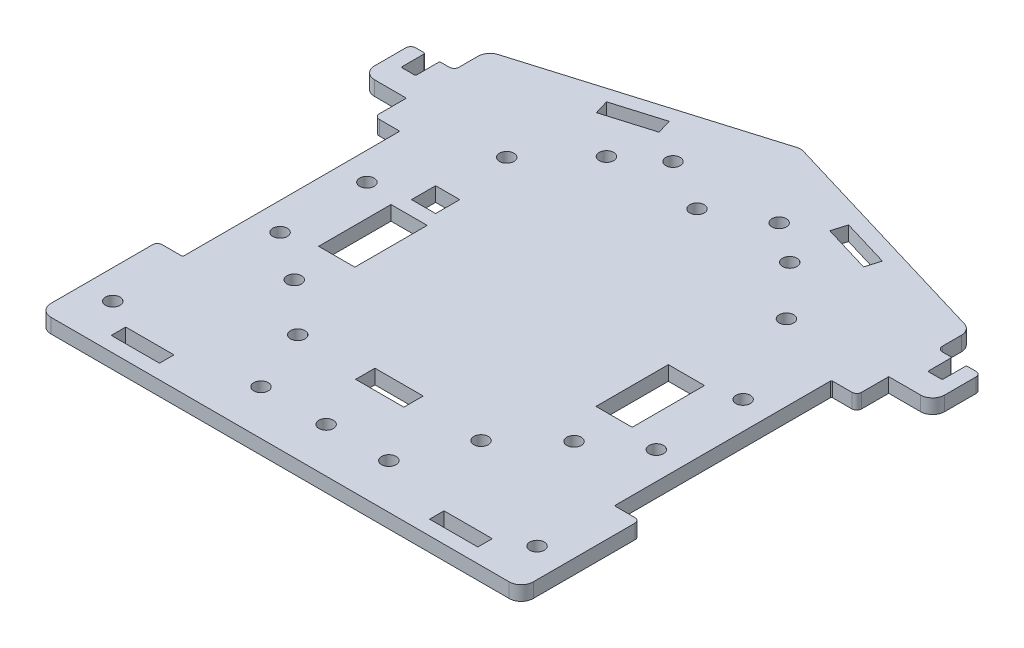
SolidWorks part; units mm, degrees
ref_plane "Alzado" through (0, 0, 0) normal (0, 0, 1) x (1, 0, 0)
ref_plane "Planta" through (0, 0, 0) normal (0, 1, 0) x (1, 0, 0)
ref_plane "Vista lateral" through (0, 0, 0) normal (1, 0, 0) x (0, 0, -1)
sketch "Croquis3" plane through (0, 0, 0) normal (0, 1, 0) x (1, 0, 0)
  line L3 (-50, -45) -> (50, -45)
  line L5 (-50, 45) -> (50, -45) construction
  line L6 (-50, -45) -> (50, 45) construction
  line L7 (-48.3179, 45.5346) -> (-0.6155, 59.8352)
  line L17 (0, 7.5742) -> (0, -7.5742) construction
  line L18 (-8.1342, 0) -> (8.1342, 0) construction
  line L21 (5, 0) -> (25, 0) construction
  line L28 (25, 7.5) -> (25, -7.5)
  line L29 (25, -7.5) -> (32.5, -7.5)
  line L30 (32.5, -7.5) -> (32.5, 7.5)
  line L31 (32.5, 7.5) -> (25, 7.5)
  line L32 (-32.5, -7.5) -> (-32.5, 7.5)
  line L33 (-25, -7.5) -> (-32.5, -7.5)
  line L34 (-25, 7.5) -> (-25, -7.5)
  line L35 (-32.5, 7.5) -> (-25, 7.5)
  line L36 (-24.4667, 52.6849) -> (-23.5953, 49.7782) construction
  line L45 (-50.1, 38.1899) -> (-47.1, 38.1899) construction
  line L46 (-50.1, 38.1899) -> (-53.1, 38.1899)
  line L47 (-53.1, 38.1899) -> (-53.1, 33.1899)
  line L48 (-53.1, 33.1899) -> (-56.1, 33.1899)
  line L49 (-56.1, 33.1899) -> (-56.1, 38.1899)
  line L50 (-56.1, 38.1899) -> (-59.1, 38.1899)
  line L51 (-59.1, 38.1899) -> (-59.1, 30.6899)
  line L52 (-56.6, 28.1899) -> (-50, 28.1899)
  line L53 (-50.1, 43.1399) -> (-50.1, 38.1899)
  line L54 (-50, 28.1899) -> (-50, -45)
  line L55 (50, 28.1899) -> (50, -45)
  line L56 (56.6, 28.1899) -> (50, 28.1899)
  line L57 (59.1, 38.1899) -> (59.1, 30.6899)
  line L58 (56.1, 38.1899) -> (59.1, 38.1899)
  line L59 (56.1, 33.1899) -> (56.1, 38.1899)
  line L60 (53.1, 33.1899) -> (56.1, 33.1899)
  line L61 (53.1, 38.1899) -> (53.1, 33.1899)
  line L62 (50.1, 38.1899) -> (53.1, 38.1899)
  line L69 (-23.5953, 49.7782) -> (-18.5953, 51.2772)
  line L70 (-18.5953, 51.2772) -> (-17.696, 48.2772)
  line L71 (-23.5953, 49.7782) -> (-28.5953, 48.2793)
  line L72 (-28.5953, 48.2793) -> (-27.696, 45.2793)
  line L73 (-27.696, 45.2793) -> (-17.696, 48.2772)
  line L74 (28.5953, 48.2793) -> (27.696, 45.2793)
  line L75 (23.5953, 49.7782) -> (28.5953, 48.2793)
  line L76 (23.5953, 49.7782) -> (18.5953, 51.2772)
  line L77 (18.5953, 51.2772) -> (17.696, 48.2772)
  line L78 (27.696, 45.2793) -> (17.696, 48.2772)
  line L79 (48.3179, 45.5346) -> (0.6155, 59.8352)
  line L80 (50.1, 43.1399) -> (50.1, 38.1899)
  arc A5 (-48.3179, 45.5346) -> (-50.1, 43.1399) centre (-47.6, 43.1399) ccw
  arc A7 (-59.1, 30.6899) -> (-56.6, 28.1899) centre (-56.6, 30.6899) ccw
  arc A8 (59.1, 30.6899) -> (56.6, 28.1899) centre (56.6, 30.6899) cw
  arc A9 (48.3179, 45.5346) -> (50.1, 43.1399) centre (47.6, 43.1399) cw
  arc A10 (-0.6155, 59.8352) -> (0.6155, 59.8352) centre (0, 57.2969) cw
  point P0 (0, 0)
  point P16 (0, 0)
  point P18 (0, 0)
  point P26 (21.4666, 4.1883)
  point P29 (0, 0)
  point P39 (25, 0)
  point P53 (0, 60)
  point P59 (-23.5953, 49.7782)
  point P60 (-23.5953, 49.7782)
  point P66 (-50.1, 38.1899)
  point P78 (-59.1, 28.1899)
  dimension "D29" = 2.5
  dimension "D1" = 90
  dimension "D2" = 100
  dimension "D5" = 15
  dimension "D14" = 20
  dimension "D15" = 7.5
  dimension "D16" = 15
  dimension "D18" = 3
  dimension "D19" = 3
  dimension "D20" = 5
  dimension "D21" = 5
  dimension "D22" = 4.95
  dimension "D23" = 10
  dimension "D24" = 5
  dimension "D25" = 5
  dimension "D26" = 3
  dimension "D27" = 3
  dimension "D28" = 3
extrude "Saliente-Extruir1" add sketch "Croquis3" along normal blind 3
sketch "Croquis4" plane through (0, 3, 0) normal (0, 1, 0) x (1, 0, 0)
  line L0 (-32.5, 7.5) -> (-32.5, -7.5) construction
  line L1 (44.75, 21.57) -> (58.75, 21.57)
  line L2 (44.75, 21.57) -> (44.75, -23.43)
  line L3 (44.75, -23.43) -> (58.75, -23.43)
  line L4 (58.75, 21.57) -> (58.75, -23.43)
  line L5 (44.75, 21.57) -> (58.75, -23.43) construction
  line L6 (44.75, -23.43) -> (58.75, 21.57) construction
  line L7 (0, 9.5449) -> (0, -9.5449) construction
  line L8 (-44.75, -23.43) -> (-58.75, -23.43)
  line L9 (-58.75, 21.57) -> (-58.75, -23.43)
  line L10 (-44.75, 21.57) -> (-58.75, 21.57)
  line L11 (-44.75, 21.57) -> (-44.75, -23.43)
  line L12 (-28.75, 7.5) -> (-28.75, 24) construction
  line L13 (-25, 7.5) -> (-32.5, 7.5) construction
  line L14 (-8.1155, 0) -> (8.1155, 0) construction
  line L16 (-38, -45) -> (-28, -45)
  line L17 (-50, -45) -> (50, -45) construction
  line L18 (-38, -45) -> (-38, -42)
  line L19 (-38, -42) -> (-28, -42)
  line L20 (-28, -45) -> (-28, -42)
  line L24 (38, -42) -> (28, -42)
  line L25 (28, -45) -> (28, -42)
  line L26 (38, -45) -> (28, -45)
  line L27 (38, -45) -> (38, -42)
  line L28 (-50, -38.7033) -> (50, -38.7033) construction
  line L29 (-50, 28.1899) -> (-50, -45) construction
  line L31 (-44.75, 9) -> (-33.25, 9) construction
  line L32 (50, -45) -> (50, 28.1899) construction
  line L35 (-44.75, 9) -> (-44.75, -9) construction
  line L36 (-32.75, -15.8561) -> (32.75, -15.8561) construction
  line L37 (-44.75, -9) -> (-33.25, -9) construction
  line L38 (-33.25, 9) -> (-33.25, -9) construction
  circle A6 centre (0.25, -38.7033) radius 1.5
  circle A18 centre (-39, 9) radius 1.5
  circle A19 centre (39, 9) radius 1.5
  circle A20 centre (39, -9) radius 1.5
  circle A21 centre (-39, -9) radius 1.5
  circle A24 centre (-43.981, -38.7033) radius 1.5
  circle A25 centre (-13.25, -38.7033) radius 1.5
  circle A26 centre (13.25, -38.7033) radius 1.5
  circle A27 centre (43.981, -38.7033) radius 1.5
  point P0 (51.75, -0.93)
  point P11 (0, 0)
  point P23 (0, 0)
  point P29 (-38, -45)
  point P70 (-32.5, 0)
  point P71 (-33.25, 0)
  dimension "D4" = 3
  dimension "D6" = 3
  dimension "D12" = 18
  dimension "D13" = 3
  dimension "D14" = 3
  dimension "D15" = 3
  dimension "D1" = 14
  dimension "D2" = 45
  dimension "D3" = 16.5
  dimension "D7" = 10
  dimension "D11" = 11.5
extrude "Cortar-Extruir1" cut sketch "Croquis4" against normal mid plane 6
sketch "Croquis5" plane through (0, 0, 0) normal (0, 1, 0) x (1, 0, 0)
  line L0 (-50, -45) -> (50, -45)
  line L5 (50, -45) -> (50, -45.5)
  line L6 (47.5, -48) -> (-47.5, -48)
  line L7 (-50, -45.5) -> (-50, -45)
  arc A0 (50, -45.5) -> (47.5, -48) centre (47.5, -45.5) cw
  arc A1 (-47.5, -48) -> (-50, -45.5) centre (-47.5, -45.5) cw
  point P8 (-50, -48)
  dimension "D2" = 2.5
  dimension "D1" = 3
extrude "Saliente-Extruir2" add sketch "Croquis5" along normal blind 3
fillet "Redondeo2" radius 0.25 12 edges at (53.1, 1.5, -33.1899) (56.1, 1.5, -33.1899) (56.1, 1.5, -38.1899) (53.1, 1.5, -38.1899) (-53.1, 1.5, -33.1899) (-56.1, 1.5, -33.1899) (-56.1, 1.5, -38.1899) (-53.1, 1.5, -38.1899) (44.75, 1.5, -21.57) (44.75, 1.5, 23.43) (-44.75, 1.5, 23.43) (-44.75, 1.5, -21.57)
fillet "Redondeo3" radius 1 8 edges at (-50.1, 1.5, -38.1899) (-59.1, 1.5, -38.1899) (59.1, 1.5, -38.1899) (50.1, 1.5, -38.1899) (-50, 1.5, -21.57) (50, 1.5, -21.57) (50, 1.5, 23.43) (-50, 1.5, 23.43)
sketch "Croquis6" plane through (0, 3, 0) normal (0, 1, 0) x (1, 0, 0)
  line L1 (-23.2779, -29.5559) -> (23.7221, -29.5559) construction
  line L2 (-23.2779, -29.5559) -> (-23.2779, 42.4441) construction
  line L3 (-23.2779, 42.4441) -> (23.7221, 42.4441) construction
  line L4 (23.7221, 42.4441) -> (23.7221, -29.5559) construction
  line L5 (0.2221, 42.4441) -> (0.2221, -29.5559) construction
  line L6 (-28.75, 7.5) -> (-28.75, 10.5) construction
  line L7 (-23.2779, 6.4441) -> (23.7221, 6.4441) construction
  line L12 (-25, 7.5) -> (-32.5, 7.5) construction
  line L13 (-31.25, 10.5) -> (-26.25, 10.5)
  line L14 (-26.25, 10.5) -> (-26.25, 15.5)
  line L15 (-26.25, 15.5) -> (-31.25, 15.5)
  line L16 (-31.25, 15.5) -> (-31.25, 10.5)
  line L17 (-4.7779, -23.5559) -> (5.2221, -23.5559)
  line L18 (-4.7779, -23.5559) -> (-4.7779, -27.5559)
  line L19 (-4.7779, -27.5559) -> (5.2221, -27.5559)
  line L20 (5.2221, -23.5559) -> (5.2221, -27.5559)
  line L21 (-4.7779, -23.5559) -> (5.2221, -27.5559) construction
  line L22 (-4.7779, -27.5559) -> (5.2221, -23.5559) construction
  circle A1 centre (-18.7779, -25.5559) radius 1.5
  circle A3 centre (-18.7779, 38.4441) radius 1.5
  circle A4 centre (19.2221, -25.5559) radius 1.5
  circle A5 centre (19.2221, 38.4441) radius 1.5
  point P0 (0.2221, -25.5559)
  point P8 (0.2221, -29.5559)
  point P28 (-28.75, 10.5)
  dimension "D6" = 3
  dimension "D7" = 4.5
  dimension "D8" = 4
  dimension "D1" = 10
  dimension "D2" = 47
  dimension "D3" = 72
  dimension "D4" = 3
  dimension "D5" = 5
  dimension "D9" = 5
  dimension "D10" = 4
extrude "Cortar-Extruir2" cut sketch "Croquis6" against normal mid plane 10
sketch "Croquis7" plane through (0, 3, 0) normal (0, 1, 0) x (1, 0, 0)
  line L0 (-24.5, 35.9495) -> (24.5, 35.9495) construction
  line L1 (-24.5, 35.9495) -> (-24.5, -24.0505) construction
  line L2 (-24.5, -24.0505) -> (24.5, -24.0505) construction
  line L3 (24.5, -24.0505) -> (24.5, 35.9495) construction
  line L4 (0, 0) -> (0, 12.5454) construction
  line L5 (0, -24.0505) -> (0, -21.0505) construction
  line L6 (32.5, -7.5) -> (32.5, -21.0505) construction
  line L7 (-24.5, 5.9495) -> (24.5, 5.9495) construction
  line L8 (-32.5, -11.0505) -> (32.5, -11.0505) construction
  line L9 (-32.5, -11.0505) -> (-32.5, -21.0505) construction
  line L10 (-32.5, -21.0505) -> (32.5, -21.0505) construction
  line L11 (32.5, -11.0505) -> (32.5, -21.0505) construction
  line L12 (-32.5, -11.0505) -> (32.5, -21.0505) construction
  line L13 (-32.5, -21.0505) -> (32.5, -11.0505) construction
  line L15 (32.5, 22.9495) -> (32.5, 32.9495) construction
  line L16 (-32.5, 22.9495) -> (32.5, 22.9495) construction
  line L17 (-32.5, 22.9495) -> (-32.5, 32.9495) construction
  line L18 (-14.7718, 32.9495) -> (-14.7718, 52.5589) construction
  line L19 (32.5224, 22.9639) -> (32.5224, 32.9639) construction
  line L20 (-14.7718, 52.5589) -> (15.7818, 52.5589) construction
  line L21 (15.7818, 52.5589) -> (15.7818, 32.9495) construction
  line L22 (-18.7779, 38.4441) -> (0, 38.4441) construction
  line L23 (-32.5, 32.9495) -> (-14.7718, 32.9495) construction
  line L24 (15.7818, 32.9495) -> (32.5, 32.9495) construction
  line L25 (-32.4776, 22.9639) -> (32.5224, 22.9639) construction
  line L26 (-32.4776, 22.9639) -> (-32.4776, 32.9639) construction
  line L27 (-14.9776, 32.9639) -> (-14.9776, 52.5733) construction
  line L28 (-14.9776, 52.5733) -> (15.0224, 52.5733) construction
  line L29 (15.0224, 52.5733) -> (15.0224, 32.9639) construction
  line L30 (-32.4776, 32.9639) -> (-14.9776, 32.9639) construction
  line L31 (15.0224, 32.9639) -> (32.5224, 32.9639) construction
  line L32 (-9.4776, 44.4441) -> (9.5224, 44.4441) construction
  line L33 (-14.9776, 51.9441) -> (15.0224, 51.9441) construction
  line L34 (-14.9776, 51.9441) -> (-14.9776, 36.9441) construction
  line L35 (-14.9776, 36.9441) -> (15.0224, 36.9441) construction
  line L36 (15.0224, 51.9441) -> (15.0224, 36.9441) construction
  line L37 (-14.9776, 51.9441) -> (15.0224, 36.9441) construction
  line L38 (-14.9776, 36.9441) -> (15.0224, 51.9441) construction
  circle A7 centre (29.0224, 27.9639) radius 1.5
  circle A8 centre (-29, -16.0505) radius 1.5
  circle A9 centre (29, -16.0505) radius 1.5
  circle A10 centre (-28.9776, 27.9639) radius 1.5
  circle A11 centre (-10.9776, 44.4441) radius 1.5
  circle A12 centre (11.0224, 44.4441) radius 1.5
  circle A14 centre (0, 38.4441) radius 1.5
  point P3 (0, 35.9495)
  point P12 (0, -16.0505)
  point P52 (0.0224, 44.4441)
  point P53 (0.0224, 52.5733)
  point P54 (0.0224, 44.4441)
  point P64 (0, 6.2727)
  dimension "D6" = 3.5
  dimension "D9" = 17.5
  dimension "D11" = 30
  dimension "D10" = 65
  dimension "D7" = 3
  dimension "D15" = 3
  dimension "D1" = 49
  dimension "D2" = 60
  dimension "D3" = 3
  dimension "D4" = 10
  dimension "D5" = 65
  dimension "D8" = 17.5
  dimension "D12" = 3.5
  dimension "D13" = 3.5
  dimension "D14" = 22
  dimension "D16" = 15
  dimension "D17" = 30
extrude "Cortar-Extruir4" cut sketch "Croquis7" against normal mid plane 10
